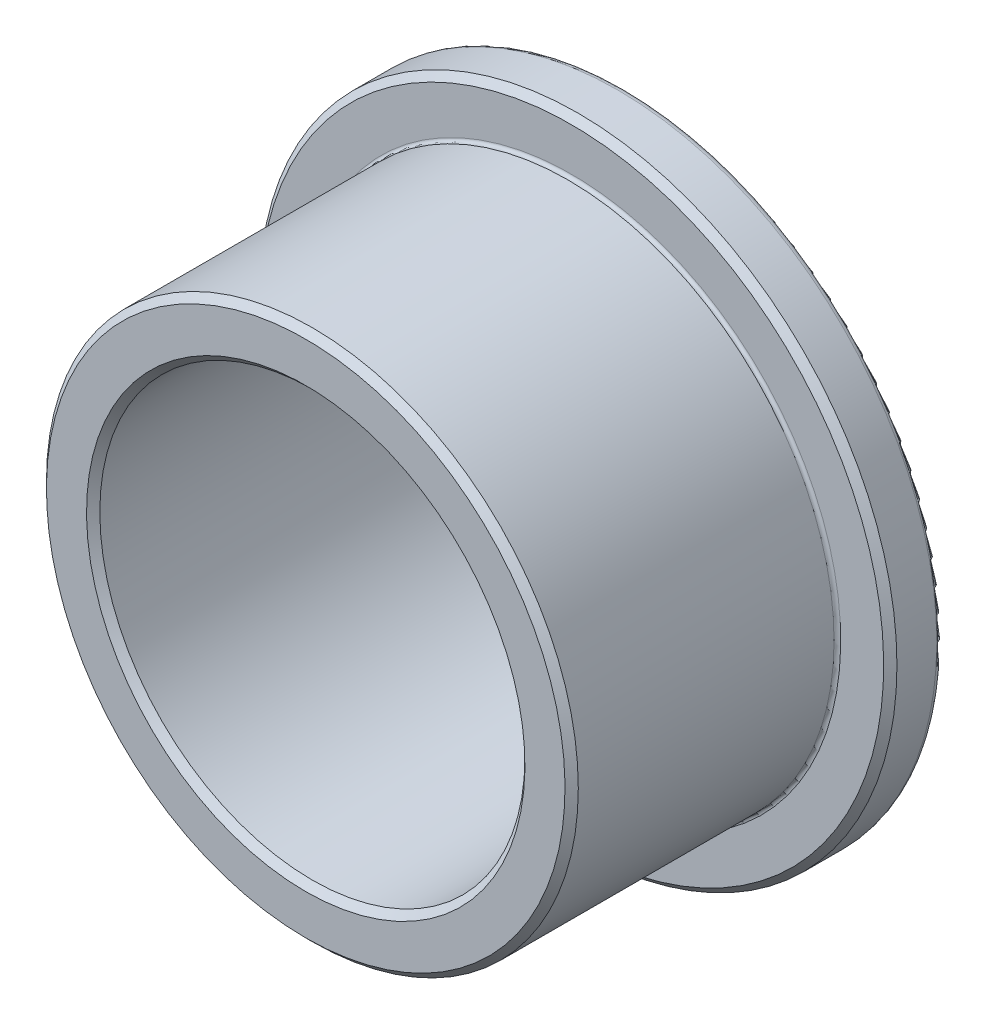
SolidWorks part; units mm, degrees
ref_plane "Front Plane" through (0, 0, 0) normal (0, 0, 1) x (1, 0, 0)
ref_plane "Top Plane" through (0, 0, 0) normal (0, 1, 0) x (1, 0, 0)
ref_plane "Right Plane" through (0, 0, 0) normal (1, 0, 0) x (0, 0, -1)
sketch "Sketch1" plane through (0, 0, 0) normal (0, 0, 1) x (1, 0, 0)
  circle A0 centre (0, 0) radius 12.7
  circle A1 centre (0, 0) radius 15.8877
  circle A2 centre (0, 0) radius 19.05
  point P5 (0, 15.8877)
  point P6 (0, 12.7)
  point P7 (0, 19.05)
  dimension "ID" = 25.4
  dimension "OD" = 31.7754
  dimension "Flange OD" = 38.1
sketch "Sketch2" plane through (0, 0, 0) normal (1, 0, 0) x (0, 0, -1)
  line L0 (9.525, 0) -> (-9.525, 0)
  line L1 (9.525, 0) -> (9.525, 19.05)
  line L2 (9.525, 19.05) -> (6.35, 19.05)
  line L3 (6.35, 19.05) -> (6.35, 15.8877)
  line L4 (6.35, 15.8877) -> (-9.525, 15.8877)
  line L5 (-9.525, 15.8877) -> (-9.525, 12.7)
  line L6 (-9.525, 12.7) -> (9.525, 12.7)
  point P4 (0, 0)
  dimension "Flange Thickness" = 3.175
  dimension "Length" = 19.05
sketch "Sketch3" plane through (0, 0, 0) normal (1, 0, 0) x (0, 0, -1)
  line L0 (9.525, 19.05) -> (6.35, 19.05) construction
  line L1 (6.35, 19.05) -> (6.35, 15.8877) construction
  line L2 (6.35, 15.8877) -> (-9.525, 15.8877) construction
  line L3 (-9.525, 12.7) -> (9.525, 12.7) construction
  line L4 (-9.525, 15.8877) -> (-9.525, 12.7) construction
  line L5 (9.525, 19.05) -> (6.35, 19.05)
  line L6 (6.35, 19.05) -> (6.35, 15.8877)
  line L7 (6.35, 15.8877) -> (-9.525, 15.8877)
  line L8 (-9.525, 12.7) -> (9.525, 12.7)
  line L9 (-9.525, 15.8877) -> (-9.525, 12.7)
  line L10 (9.525, 19.05) -> (9.525, 12.7)
revolve "Revolve1" add sketch "Sketch3" angle 360 about L0
chamfer "Chamfer1" distance 0.3969 angle 45 3 edges at (0, 19.05, -6.35) (0, 15.8877, 9.525) (0, 12.7, 9.525)
fillet "Fillet1" radius 0.3969 1 edges at (0, 19.05, -9.525)
fillet "Fillet2" radius 0.1984 1 edges at (0, 15.8877, -6.35)
equation "\"D1@Chamfer1\"=\"Flange Thickness@Sketch2\"*.125"
equation "\"D1@Fillet1\"=\"D1@Chamfer1\""
equation "\"D1@Fillet2\"=\"D1@Fillet1\"*.5"
